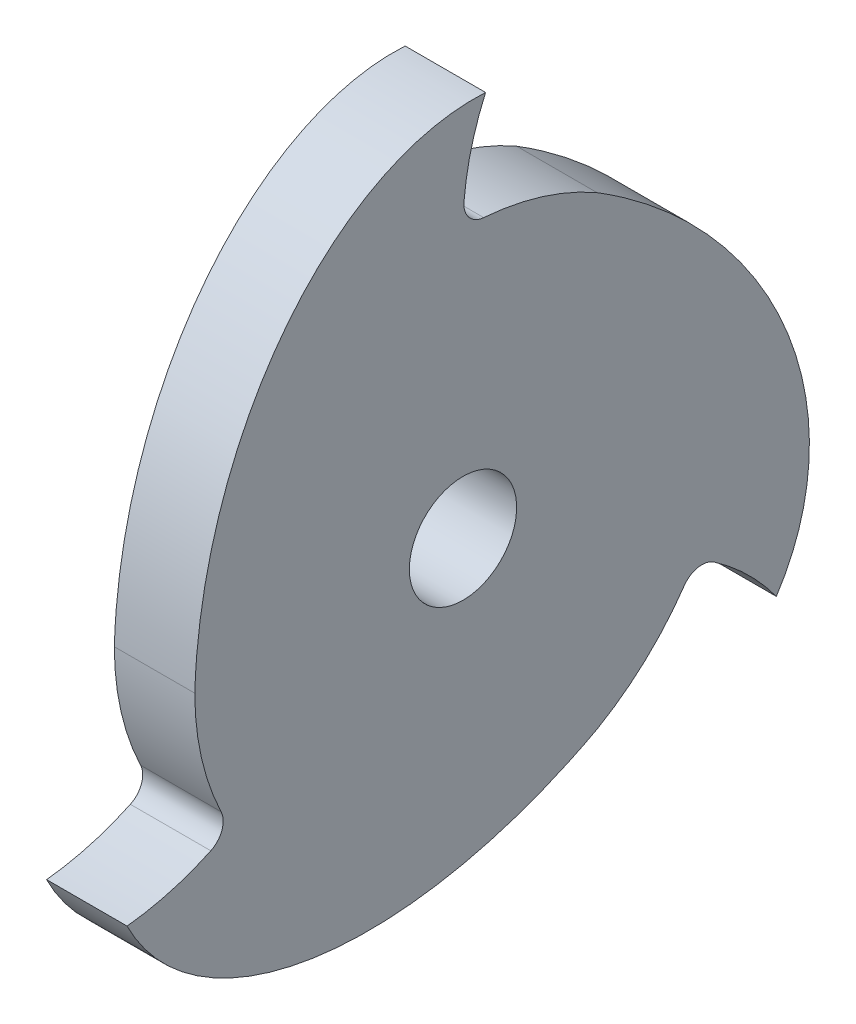
SolidWorks part; units mm, degrees
material "AISI 304"
ref_plane "Front Plane" through (0, 0, 0) normal (0, 0, 1) x (1, 0, 0)
ref_plane "Top Plane" through (0, 0, 0) normal (0, 1, 0) x (1, 0, 0)
ref_plane "Right Plane" through (0, 0, 0) normal (1, 0, 0) x (0, 0, -1)
sketch "Sketch1" plane through (0, 0, 0) normal (1, 0, 0) x (0, 0, -1)
  line L0 (0, 31.75) -> (101.4565, 31.75) construction
  line L1 (0, 0) -> (-38.4948, -22.225) construction
  line L2 (5.2388, 0) -> (-5.2388, 0) construction
  line L3 (0, 0) -> (-44.45, 0) construction
  circle A0 centre (0, 0) radius 31.75
  circle A1 centre (0, 0) radius 44.45
  arc A2 (0, 31.75) -> (2.6746, 44.3695) centre (31.1085, 31.75) cw
  arc A3 (27.4963, -15.875) -> (37.0878, -24.501) centre (11.942, -42.8158) cw
  arc A4 (-27.4963, -15.875) -> (-39.7624, -19.8685) centre (-43.0506, 11.0658) cw
  circle A5 centre (0, 0) radius 6.35
  ellipse E0 centre (0, 0) end of major axis (-2.6746, -44.3695) minor radius 31.7218 (2.6746, 44.3695) -> (-31.75, 0) ccw
  ellipse E1 centre (0, 0) end of major axis (37.0878, -24.501) minor radius 31.7218 (37.0878, -24.501) -> (15.875, 27.4963) ccw
  ellipse E2 centre (0, 0) end of major axis (-39.7624, -19.8685) minor radius 31.7218 (-39.7624, -19.8685) -> (15.875, -27.4963) ccw
  point P35 (0, 0)
  point P37 (0, 0)
  dimension "D1" = 63.5
  dimension "D2" = 88.9
  dimension "D5" = 12.7
  dimension "D3" = 30
  dimension "D4" = 3
extrude "Boss-Extrude3" add sketch "Sketch1" along normal blind 9.525
fillet "Fillet3" radius 2.54 3 edges at (4.7625, -15.875, 27.4963) (4.7625, -15.875, -27.4963) (4.7625, 31.75, 0)
